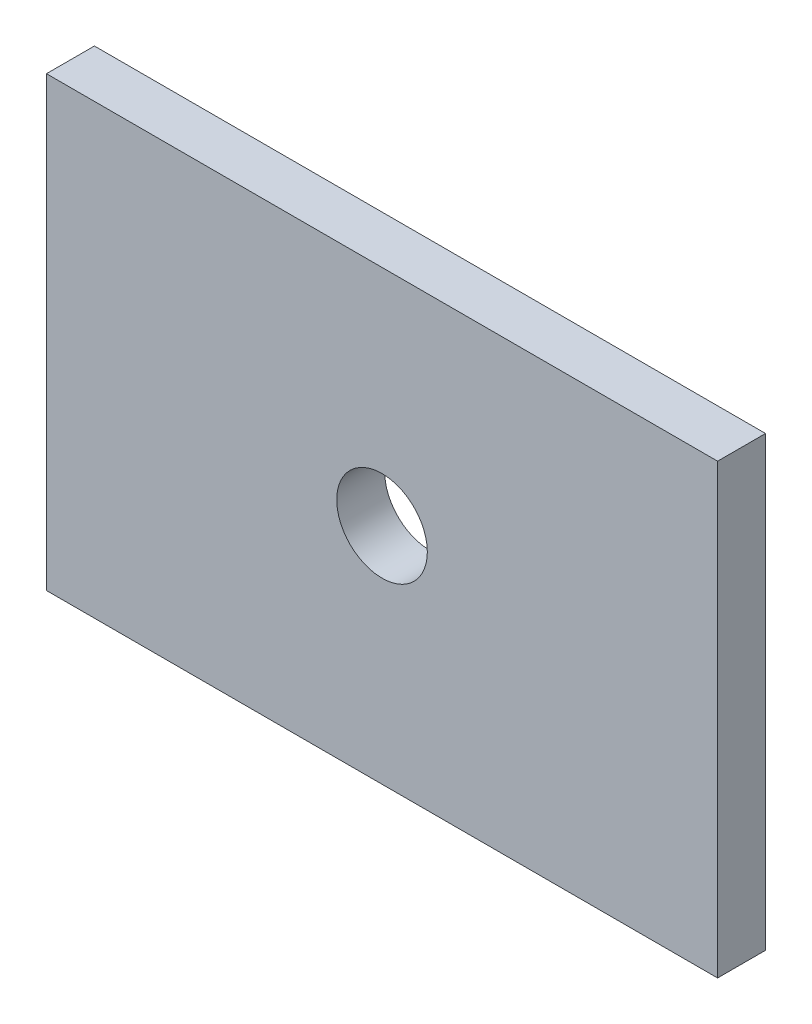
SolidWorks part; units mm, degrees
ref_plane "Front Plane" through (0, 0, 0) normal (0, 0, 1) x (1, 0, 0)
ref_plane "Top Plane" through (0, 0, 0) normal (0, 1, 0) x (1, 0, 0)
ref_plane "Right Plane" through (0, 0, 0) normal (1, 0, 0) x (0, 0, -1)
sketch "Sketch1" plane through (0, 0, 0) normal (0, 0, 1) x (1, 0, 0)
  line L1 (0, 0) -> (66.6496, 0)
  line L2 (0, 0) -> (0, 44.45)
  line L3 (0, 44.45) -> (66.6496, 44.45)
  line L4 (66.6496, 0) -> (66.6496, 44.45)
  dimension "D1" = 66.6496
  dimension "D2" = 44.45
extrude "Boss-Extrude1" add sketch "Sketch1" along normal blind 4.7625
sketch "Sketch2" plane through (0, 0, 4.7625) normal (0, 0, 1) x (1, 0, 0)
  line L0 (0, 44.45) -> (66.6496, 0) construction
  circle A0 centre (33.3248, 22.225) radius 4.5
  dimension "D1" = 9
extrude "Cut-Extrude1" cut sketch "Sketch2" against normal through all
